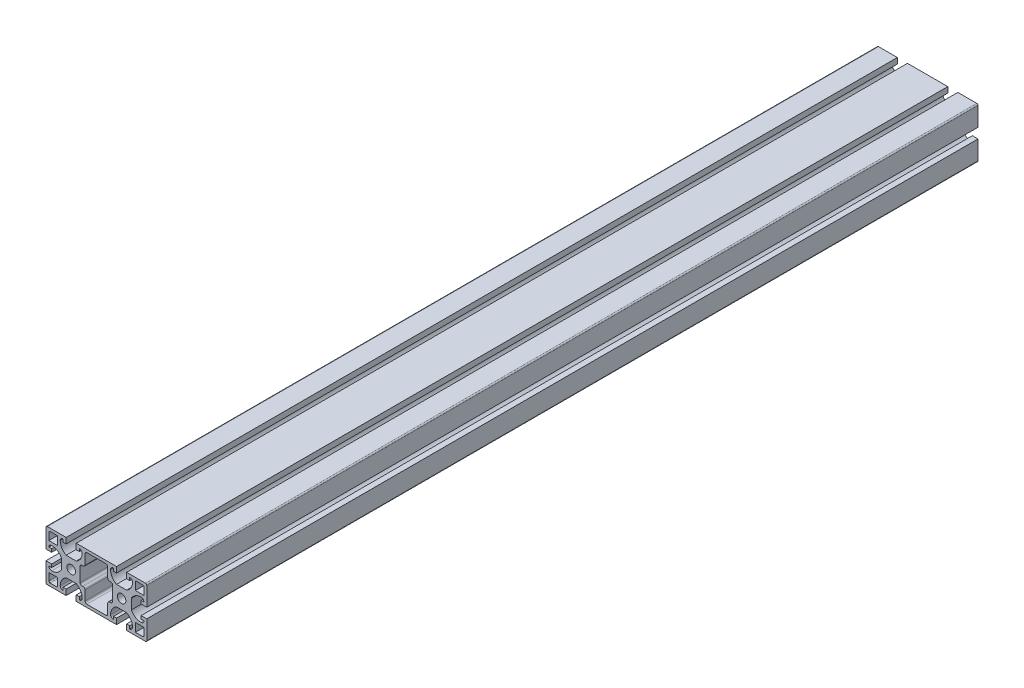
SolidWorks part; units mm, degrees
material "3.0255 (EN-AW 1350A)"
ref_plane "Płaszczyzna przednia" through (0, 0, 0) normal (0, 0, 1) x (1, 0, 0)
ref_plane "Płaszczyzna górna" through (0, 0, 0) normal (0, 1, 0) x (1, 0, 0)
ref_plane "Płaszczyzna prawa" through (0, 0, 0) normal (1, 0, 0) x (0, 0, -1)
sketch "Szkic1" plane through (0, 0, 0) normal (0, 0, 1) x (1, 0, 0)
  line L0 (0, 20) -> (0, -20) construction
  line L1 (-51.8865, 0) -> (40, 0) construction
  line L4 (-40, -19) -> (-40, 19)
  line L7 (-40, -20) -> (0, 0) construction
  line L8 (-40, 20) -> (40, -20) construction
  line L13 (20, 20) -> (20, 0) construction
  line L15 (24, 20) -> (24, 15.5)
  line L16 (24, 15.5) -> (26.4714, 15.5)
  line L21 (16, 15.5) -> (13.5286, 15.5)
  line L23 (16, 20) -> (13.5286, 20)
  line L24 (16, 20) -> (16, 15.5)
  line L25 (16, 7.75) -> (24, 7.75)
  line L26 (13.5286, 15.5) -> (13.5286, 17.75)
  line L27 (26.4714, 15.5) -> (26.4714, 17.75)
  line L28 (-24, 20) -> (-24, 15.5)
  line L29 (-26.4714, 15.5) -> (-26.4714, 17.75)
  line L30 (-24, 15.5) -> (-26.4714, 15.5)
  line L31 (-13.5286, 15.5) -> (-13.5286, 17.75)
  line L32 (-16, 15.5) -> (-13.5286, 15.5)
  line L33 (-16, 20) -> (-16, 15.5)
  line L34 (-16, 7.75) -> (-24, 7.75)
  line L35 (20, -20) -> (20, 0) construction
  line L36 (-40, -20) -> (0, 0) construction
  line L37 (-40, 20) -> (40, -20) construction
  line L38 (30.9714, -17.75) -> (36.75, -17.75)
  line L39 (-16, -7.75) -> (-24, -7.75)
  line L40 (-16, -20) -> (-16, -15.5)
  line L41 (-16, -15.5) -> (-13.5286, -15.5)
  line L42 (-13.5286, -15.5) -> (-13.5286, -17.75)
  line L43 (-24, -15.5) -> (-26.4714, -15.5)
  line L44 (-26.4714, -15.5) -> (-26.4714, -17.75)
  line L45 (-24, -20) -> (-24, -15.5)
  line L46 (26.4714, -15.5) -> (26.4714, -17.75)
  line L47 (13.5286, -15.5) -> (13.5286, -17.75)
  line L48 (16, -7.75) -> (24, -7.75)
  line L49 (16, -20) -> (16, -15.5)
  line L50 (16, -15.5) -> (13.5286, -15.5)
  line L51 (24, -15.5) -> (26.4714, -15.5)
  line L52 (24, -20) -> (24, -15.5)
  line L53 (40, -20) -> (0, 20) construction
  line L54 (35.5, 6.4714) -> (37.75, 6.4714)
  line L55 (35.5, 4) -> (35.5, 6.4714)
  line L56 (40, 4) -> (35.5, 4)
  line L57 (40, -4) -> (35.5, -4)
  line L58 (35.5, -4) -> (35.5, -6.4714)
  line L59 (35.5, -6.4714) -> (37.75, -6.4714)
  line L60 (27.75, 4) -> (27.75, -4)
  line L61 (-35.5, -6.4714) -> (-37.75, -6.4714)
  line L62 (-37.75, -4) -> (-35.5, -4)
  line L63 (-35.5, -4) -> (-35.5, -6.4714)
  line L64 (-35.5, 4) -> (-35.5, 6.4714)
  line L65 (-35.5, 6.4714) -> (-37.75, 6.4714)
  line L66 (-37.75, 4) -> (-35.5, 4)
  line L67 (-27.75, 4) -> (-27.75, -4)
  line L68 (-37.75, 4) -> (-37.75, -4)
  line L69 (40, -4) -> (40, -19)
  line L70 (40, 19) -> (40, 4)
  line L71 (-39, -20) -> (-24, -20)
  line L72 (-16, -20) -> (16, -20)
  line L73 (24, -20) -> (39, -20)
  line L74 (13.5286, 20) -> (-16, 20)
  line L75 (-24, 20) -> (-39, 20)
  line L76 (24, 20) -> (39, 20)
  line L77 (10.5286, 7.0902) -> (11.4095, 7.0902)
  line L78 (-7.5286, -17.75) -> (7.5286, -17.75)
  line L79 (-9.0286, -16.25) -> (-9.0286, -8.5902)
  line L80 (-7.5286, 17.75) -> (7.5286, 17.75)
  line L81 (9.0286, -16.25) -> (9.0286, -8.5902)
  line L82 (-9.0286, -17.75) -> (9.0286, 17.75) construction
  line L83 (-9.0286, 17.75) -> (9.0286, -17.75) construction
  line L84 (-11.4095, -7.0902) -> (-10.5286, -7.0902)
  line L85 (-12.9095, -5.5902) -> (-12.9095, 5.5902)
  line L86 (-11.4095, 7.0902) -> (-10.5286, 7.0902)
  line L87 (12.9095, -5.5902) -> (12.9095, 5.5902)
  line L88 (-12.9095, -7.0902) -> (0, 0) construction
  line L89 (-12.9095, 7.0902) -> (12.9095, -7.0902) construction
  line L90 (-9.0286, 8.5902) -> (-9.0286, 16.25)
  line L91 (-9.0286, 4.5143) -> (-9.0286, 4.9587)
  line L92 (-9.0286, -4.9587) -> (-9.0286, -4.5143)
  line L93 (9.0286, 8.5902) -> (9.0286, 16.25)
  line L94 (10.5286, -7.0902) -> (11.4095, -7.0902)
  line L96 (0, 0) -> (12.9095, 7.0902) construction
  line L98 (37.75, -10.9714) -> (37.75, -16.75)
  line L99 (30.9714, 10.9714) -> (37.75, 10.9714)
  line L100 (30.9714, 10.9714) -> (30.9714, 17.75)
  line L101 (30.9714, 17.75) -> (36.75, 17.75)
  line L102 (37.75, 10.9714) -> (37.75, 16.75)
  line L103 (30.9714, 10.9714) -> (37.75, 17.75) construction
  line L104 (30.9714, 17.75) -> (37.75, 10.9714) construction
  line L105 (30.9714, -10.9714) -> (37.75, -10.9714)
  line L106 (30.9714, -10.9714) -> (30.9714, -17.75)
  line L107 (-30.9714, -10.9714) -> (-30.9714, -17.75)
  line L108 (-30.9714, -10.9714) -> (-37.75, -10.9714)
  line L109 (-37.75, -10.9714) -> (-37.75, -16.75)
  line L110 (-30.9714, -17.75) -> (-36.75, -17.75)
  line L111 (-30.9714, 17.75) -> (-36.75, 17.75)
  line L112 (-37.75, 10.9714) -> (-37.75, 16.75)
  line L113 (-30.9714, 10.9714) -> (-37.75, 10.9714)
  line L114 (-30.9714, 10.9714) -> (-30.9714, 17.75)
  circle A0 centre (-20, 0) radius 3.4
  circle A1 centre (20, 0) radius 3.4
  arc A2 (26.4714, 17.75) -> (28.7214, 15.5) centre (26.4714, 15.5) cw
  arc A3 (28.7214, 15.5) -> (24, 7.75) centre (20, 15.5) cw
  arc A4 (13.5286, 17.75) -> (11.2786, 15.5) centre (13.5286, 15.5) ccw
  arc A5 (11.2786, 15.5) -> (16, 7.75) centre (20, 15.5) ccw
  arc A6 (-26.4714, 17.75) -> (-28.7214, 15.5) centre (-26.4714, 15.5) ccw
  arc A7 (-13.5286, 17.75) -> (-11.2786, 15.5) centre (-13.5286, 15.5) cw
  arc A8 (-11.2786, 15.5) -> (-16, 7.75) centre (-20, 15.5) cw
  arc A9 (-28.7214, 15.5) -> (-24, 7.75) centre (-20, 15.5) ccw
  arc A10 (-28.7214, -15.5) -> (-24, -7.75) centre (-20, -15.5) cw
  arc A11 (-11.2786, -15.5) -> (-16, -7.75) centre (-20, -15.5) ccw
  arc A12 (-13.5286, -17.75) -> (-11.2786, -15.5) centre (-13.5286, -15.5) ccw
  arc A13 (-26.4714, -17.75) -> (-28.7214, -15.5) centre (-26.4714, -15.5) cw
  arc A14 (11.2786, -15.5) -> (16, -7.75) centre (20, -15.5) cw
  arc A15 (13.5286, -17.75) -> (11.2786, -15.5) centre (13.5286, -15.5) cw
  arc A16 (28.7214, -15.5) -> (24, -7.75) centre (20, -15.5) ccw
  arc A17 (26.4714, -17.75) -> (28.7214, -15.5) centre (26.4714, -15.5) ccw
  arc A18 (35.5, 8.7214) -> (27.75, 4) centre (35.5, 0) ccw
  arc A19 (37.75, 6.4714) -> (35.5, 8.7214) centre (35.5, 6.4714) ccw
  arc A20 (37.75, -6.4714) -> (35.5, -8.7214) centre (35.5, -6.4714) cw
  arc A21 (35.5, -8.7214) -> (27.75, -4) centre (35.5, 0) cw
  arc A22 (-35.5, -8.7214) -> (-27.75, -4) centre (-35.5, 0) ccw
  arc A23 (-37.75, -6.4714) -> (-35.5, -8.7214) centre (-35.5, -6.4714) ccw
  arc A24 (-37.75, 6.4714) -> (-35.5, 8.7214) centre (-35.5, 6.4714) cw
  arc A25 (-35.5, 8.7214) -> (-27.75, 4) centre (-35.5, 0) cw
  arc A26 (-10.5286, 7.0902) -> (-9.0286, 8.5902) centre (-10.5286, 8.5902) ccw
  arc A27 (-9.0286, -8.5902) -> (-10.5286, -7.0902) centre (-10.5286, -8.5902) ccw
  arc A28 (11.4095, -7.0902) -> (12.9095, -5.5902) centre (11.4095, -5.5902) ccw
  arc A29 (9.0286, -8.5902) -> (10.5286, -7.0902) centre (10.5286, -8.5902) cw
  arc A30 (7.5286, -17.75) -> (9.0286, -16.25) centre (7.5286, -16.25) ccw
  arc A31 (-7.5286, -17.75) -> (-9.0286, -16.25) centre (-7.5286, -16.25) cw
  arc A32 (-11.4095, -7.0902) -> (-12.9095, -5.5902) centre (-11.4095, -5.5902) cw
  arc A33 (-12.9095, 5.5902) -> (-11.4095, 7.0902) centre (-11.4095, 5.5902) cw
  arc A34 (-9.0286, 16.25) -> (-7.5286, 17.75) centre (-7.5286, 16.25) cw
  arc A35 (7.5286, 17.75) -> (9.0286, 16.25) centre (7.5286, 16.25) cw
  arc A36 (11.4095, 7.0902) -> (12.9095, 5.5902) centre (11.4095, 5.5902) cw
  arc A37 (10.5286, 7.0902) -> (9.0286, 8.5902) centre (10.5286, 8.5902) cw
  arc A38 (-40, 19) -> (-39, 20) centre (-39, 19) cw
  arc A39 (-39, -20) -> (-40, -19) centre (-39, -19) cw
  arc A40 (39, -20) -> (40, -19) centre (39, -19) ccw
  arc A41 (39, 20) -> (40, 19) centre (39, 19) cw
  arc A42 (36.75, 17.75) -> (37.75, 16.75) centre (36.75, 16.75) cw
  arc A43 (36.75, -17.75) -> (37.75, -16.75) centre (36.75, -16.75) ccw
  arc A44 (-36.75, -17.75) -> (-37.75, -16.75) centre (-36.75, -16.75) cw
  arc A45 (-36.75, 17.75) -> (-37.75, 16.75) centre (-36.75, 16.75) ccw
  point P5 (0, 0)
  point P17 (0, 0)
  point P30 (24, 17.75)
  point P108 (0, 0)
  point P124 (-9.0286, 7.0902)
  point P132 (9.0286, -7.0902)
  point P156 (9.0286, 7.0902)
  point P161 (40, 20)
  point P162 (34.3607, 14.3607)
  dimension "D4" = 6.8
  dimension "D5" = 12.25
  dimension "D9" = 11
  dimension "D11" = 1.5
  dimension "D12" = 1
  dimension "D16" = 1
  dimension "D1" = 80
  dimension "D2" = 40
  dimension "D3" = 40
  dimension "D6" = 2.25
  dimension "D7" = 8
  dimension "D8" = 4.5
  dimension "D10" = 14.1804
  dimension "D13" = 2.25
  dimension "D14" = 2.25
  dimension "D15" = 2.25
extrude "Dodanie-wyciągnięcie1" add sketch "Szkic1" along normal blind 660 contours A20 A21 L60 A18 A19 L54 L55 L56 L70 L76 L15 L16 L27 A2 A3 L25 A5 A4 L26 L21 L24 L23 L74 L33 L32 L31 A7 A8 L34 A9 A6 L29 L30 L28 L75 L4 L71 L45 L43 L44 A13 A10 L39 A11 A12 L42 L41 L40 L72 L49 L50
sketch "Szkic2" plane through (0, 0, 660) normal (0, 0, 1) x (1, 0, 0)
  line L0 (-37.75, 4) -> (-37.75, -4) construction
  line L1 (-40, -4) -> (-37.75, -4)
  line L2 (-40, -4) -> (-40, 4)
  line L3 (-40, 4) -> (-37.75, 4)
  line L4 (-37.75, -4) -> (-37.75, 4)
  line L5 (-40, -4) -> (-37.75, 4) construction
  line L6 (-40, 4) -> (-37.75, -4) construction
  line L7 (-37.75, 4) -> (-35.5, 4) construction
  line L8 (-40, -19) -> (-40, 19) construction
  line L10 (-37.75, -4) -> (-35.5, -4) construction
  point P0 (-38.875, 0)
extrude "Wytnij-wyciągnięcie1" cut sketch "Szkic2" against normal through all
